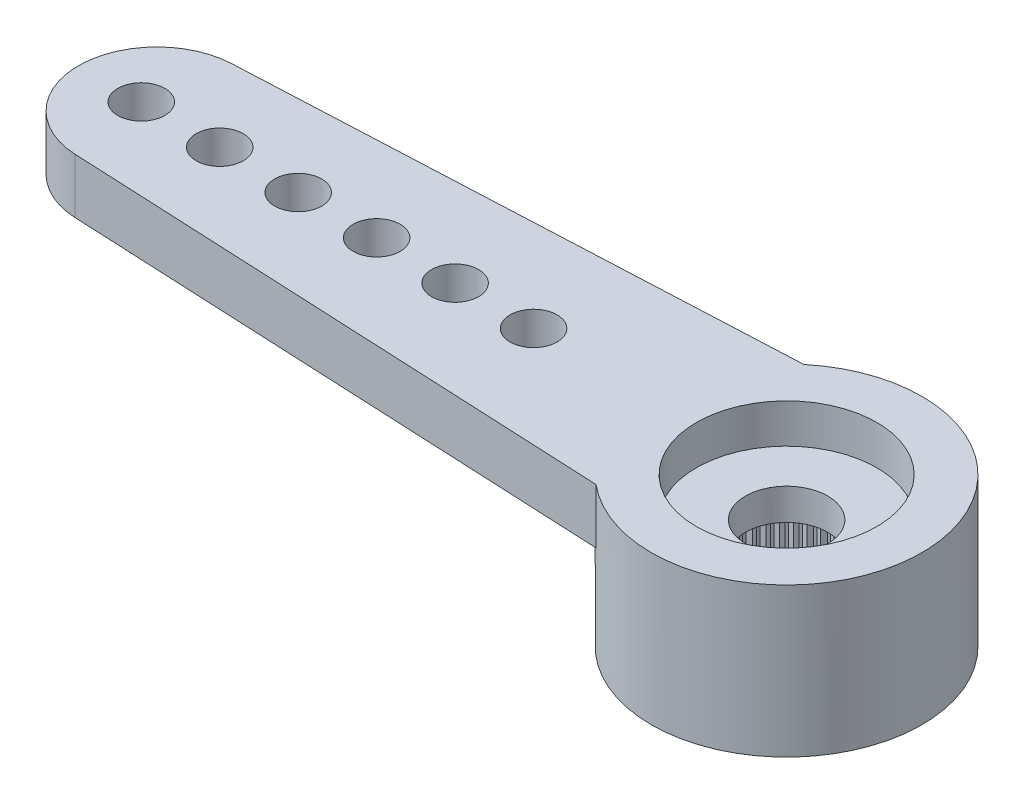
SolidWorks part; units mm, degrees
material "PVC Rígido"
ref_plane "Plano frontal" through (0, 0, 0) normal (0, 0, 1) x (1, 0, 0)
ref_plane "Plano superior" through (0, 0, 0) normal (0, 1, 0) x (1, 0, 0)
ref_plane "Plano direito" through (0, 0, 0) normal (1, 0, 0) x (0, 0, -1)
sketch "Esboço1" plane through (0, 0, 0) normal (0, 1, 0) x (1, 0, 0)
  line L0 (0, 0) -> (-16.05, 0) construction
  line L1 (-16.1435, 1.9978) -> (-2.2091, 2.65)
  line L2 (-2.2091, -2.65) -> (-16.1435, -1.9978)
  arc A0 (-2.2091, -2.65) -> (-2.2091, 2.65) centre (0, 0) ccw
  arc A1 (-16.1435, 1.9978) -> (-16.1435, -1.9978) centre (-16.05, 0) ccw
  dimension "D1" = 6.9
  dimension "D2" = 4
  dimension "D3" = 21.5
  dimension "D4" = 5.3
extrude "Ressalto-extrusão1" add sketch "Esboço1" against normal blind 1.4
sketch "Esboço2" plane through (0, -1.4, 0) normal (0, -1, 0) x (1, 0, 0)
  arc A0 (-2.2091, -2.65) -> (-2.2091, 2.65) centre (0, 0) ccw construction
  circle A1 centre (0, 0) radius 3.45
extrude "Ressalto-extrusão2" add sketch "Esboço2" along normal offset from surface (2.4 mm away) 3.8 up to face at (-8.2381, 0, 0)
hole_wizard "Furo4" positions "Esboço9" profile "Esboço10" legacy end condition through all
sketch "Esboço9" plane through (0, 0, 0) normal (0, 1, 0) x (1, 0, 0)
  line L1 (-16.45, 0) -> (0, 0) construction
  arc A2 (-16.1435, 1.9978) -> (-16.1435, -1.9978) centre (-16.05, 0) ccw construction
  point P0 (-16.45, 0)
  point P19 (-18.05, 0)
  dimension "D1" = 1.6
sketch "Esboço10" plane through (-16.45, 0, 0) normal (1, 0, 0) x (0, 0, 1)
  line L0 (0, 0) -> (0, 3.8)
  line L1 (0, 3.8) -> (0.6, 3.8)
  line L2 (0.6, 3.8) -> (0.6, 0)
  line L3 (0.6, 0) -> (0, 0)
  line L4 (0, 110) -> (0, -10) construction
  dimension "Diameter" = 1.2
  dimension "Depth" = 3.8
pattern_linear "Padrão linear1" count 6 spacing 2 along (1, 0, 0) of "Furo4"
hole_wizard "Furo1" positions "Esboço3" profile "Esboço4" legacy
sketch "Esboço3" plane through (0, -3.8, 0) normal (0, -1, 0) x (-1, 0, 0)
  point P0 (0, 0)
sketch "Esboço4" plane through (0, -3.8, 0) normal (1, 0, 0) x (0, 0, -1)
  line L0 (0, 0) -> (0, 2)
  line L1 (0, 2) -> (2.475, 2)
  line L2 (2.475, 2) -> (2.475, 0)
  line L3 (2.475, 0) -> (0, 0)
  line L4 (0, 110) -> (0, -10) construction
  dimension "Diameter" = 4.95
  dimension "Depth" = 2
hole_wizard "Furo2" positions "Esboço5" profile "Esboço6" legacy
sketch "Esboço5" plane through (0, 0, 0) normal (0, 1, 0) x (1, 0, 0)
  point P0 (0, 0)
sketch "Esboço6" plane through (0, 0, 0) normal (1, 0, 0) x (0, 0, 1)
  line L0 (0, 0) -> (0, 1)
  line L1 (0, 1) -> (2.3, 1)
  line L2 (2.3, 1) -> (2.3, 0)
  line L3 (2.3, 0) -> (0, 0)
  line L4 (0, 110) -> (0, -10) construction
  dimension "Diameter" = 4.6
  dimension "Depth" = 1
hole_wizard "Furo3" positions "Esboço7" profile "Esboço8" legacy end condition through all
sketch "Esboço7" plane through (0, 0, 0) normal (0, 1, 0) x (1, 0, 0)
  point P0 (0, 0)
sketch "Esboço8" plane through (0, 0, 0) normal (1, 0, 0) x (0, 0, 1)
  line L0 (0, 0) -> (0, 3.8)
  line L1 (0, 3.8) -> (1.05, 3.8)
  line L2 (1.05, 3.8) -> (1.05, 0)
  line L3 (1.05, 0) -> (0, 0)
  line L4 (0, 110) -> (0, -10) construction
  dimension "Diameter" = 2.1
  dimension "Depth" = 3.8
sketch "Esboço11" plane through (0, -3.8, 0) normal (0, -1, 0) x (1, 0, 0)
  line L0 (-0.0981, 2.4731) -> (0, 2.375)
  line L1 (0, 2.375) -> (0.0981, 2.4731)
  line L2 (0, 0) -> (0, 2.475) construction
  circle A0 centre (0, 0) radius 2.375 construction
  circle A1 centre (0, 0) radius 2.475
  arc A2 (0.0981, 2.4731) -> (-0.0981, 2.4731) centre (0, 0) ccw
  dimension "D3" = 4.75
  dimension "D2" = 0.1
  dimension "D1" = 0
extrude "Ressalto-extrusão3" add sketch "Esboço11" against normal up to surface (2 mm away) up to face at (0, -1.8, 1.05)
pattern_circular "PadrãoCircular1" count 60 over 360 about axis through (0, 0, 0) along (0, 1, 0) of "Ressalto-extrusão3"
